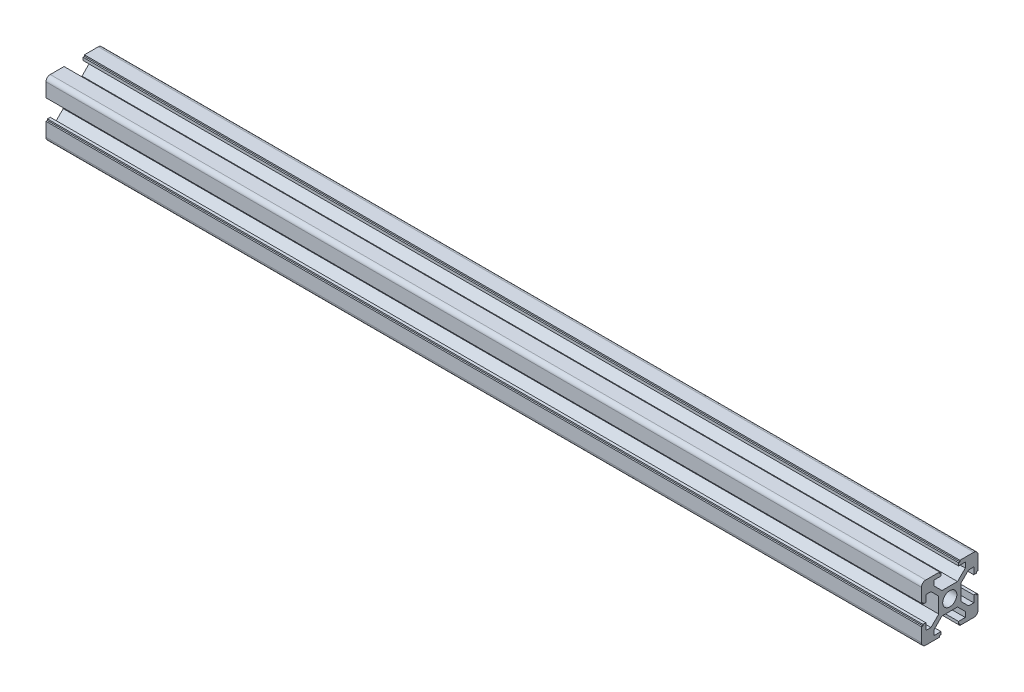
SolidWorks part; units mm, degrees
ref_plane "前视基准面" through (0, 0, 0) normal (0, 0, 1) x (1, 0, 0)
ref_plane "上视基准面" through (0, 0, 0) normal (0, 1, 0) x (1, 0, 0)
ref_plane "右视基准面" through (0, 0, 0) normal (1, 0, 0) x (0, 0, -1)
other "Configuration Table"
sketch "草图1" plane through (0, 0, 0) normal (0, 1, 0) x (1, 0, 0)
  line L0 (0, 0) -> (310, 0)
  dimension "D1" = 310
other "铝型材 20 X 20 X R1.5(1)"
ref_plane "基准面1" through (0, 0, 0) normal (1, 0, 0) x (0, 0, -1)
sketch "Sketch1" plane through (0, 0, 0) normal (1, 0, 0) x (0, 0, -1)
  line L0 (-3.6, 10) -> (-3.6, 9.5)
  line L1 (-3.6, 9.5) -> (-3.1, 9.5)
  line L2 (-3.1, 9.5) -> (-3.1, 8.5)
  line L3 (-3.1, 8.5) -> (-5.5, 8.5)
  line L4 (-8.5, -10) -> (-3.6, -10)
  line L5 (-10, -8.5) -> (-10, -3.6)
  line L6 (8.5, 10) -> (3.6, 10)
  line L7 (10, 8.5) -> (10, 3.6)
  line L8 (0, 14.8756) -> (0, 0) construction
  line L9 (0, 0) -> (14.1675, 0) construction
  line L10 (-5.5, 8.5) -> (-5.5, 6.65)
  line L11 (-5.5, 6.65) -> (-2.75, 3.9)
  line L12 (-2.75, 3.9) -> (2.75, 3.9)
  line L13 (5.5, 6.65) -> (2.75, 3.9)
  line L14 (5.5, 8.5) -> (5.5, 6.65)
  line L15 (3.1, 8.5) -> (5.5, 8.5)
  line L16 (3.1, 9.5) -> (3.1, 8.5)
  line L17 (3.6, 9.5) -> (3.1, 9.5)
  line L18 (3.6, 10) -> (3.6, 9.5)
  line L19 (-3.6, 10) -> (-8.5, 10)
  line L20 (10, 3.6) -> (9.5, 3.6)
  line L21 (9.5, 3.6) -> (9.5, 3.1)
  line L22 (9.5, 3.1) -> (8.5, 3.1)
  line L23 (8.5, 3.1) -> (8.5, 5.5)
  line L24 (8.5, 5.5) -> (6.65, 5.5)
  line L25 (6.65, 5.5) -> (3.9, 2.75)
  line L26 (3.9, 2.75) -> (3.9, -2.75)
  line L27 (6.65, -5.5) -> (3.9, -2.75)
  line L28 (8.5, -5.5) -> (6.65, -5.5)
  line L29 (8.5, -3.1) -> (8.5, -5.5)
  line L30 (9.5, -3.1) -> (8.5, -3.1)
  line L31 (9.5, -3.6) -> (9.5, -3.1)
  line L32 (10, -3.6) -> (9.5, -3.6)
  line L33 (3.6, -10) -> (3.6, -9.5)
  line L34 (3.6, -9.5) -> (3.1, -9.5)
  line L35 (3.1, -9.5) -> (3.1, -8.5)
  line L36 (3.1, -8.5) -> (5.5, -8.5)
  line L37 (5.5, -8.5) -> (5.5, -6.65)
  line L38 (5.5, -6.65) -> (2.75, -3.9)
  line L39 (2.75, -3.9) -> (-2.75, -3.9)
  line L40 (-5.5, -6.65) -> (-2.75, -3.9)
  line L41 (-5.5, -8.5) -> (-5.5, -6.65)
  line L42 (-3.1, -8.5) -> (-5.5, -8.5)
  line L43 (-3.1, -9.5) -> (-3.1, -8.5)
  line L44 (-3.6, -9.5) -> (-3.1, -9.5)
  line L45 (-3.6, -10) -> (-3.6, -9.5)
  line L46 (-10, -3.6) -> (-9.5, -3.6)
  line L47 (-9.5, -3.6) -> (-9.5, -3.1)
  line L48 (-9.5, -3.1) -> (-8.5, -3.1)
  line L49 (-8.5, -3.1) -> (-8.5, -5.5)
  line L50 (-8.5, -5.5) -> (-6.65, -5.5)
  line L51 (-6.65, -5.5) -> (-3.9, -2.75)
  line L52 (-3.9, -2.75) -> (-3.9, 2.75)
  line L53 (-6.65, 5.5) -> (-3.9, 2.75)
  line L54 (-8.5, 5.5) -> (-6.65, 5.5)
  line L55 (-8.5, 3.1) -> (-8.5, 5.5)
  line L56 (-9.5, 3.1) -> (-8.5, 3.1)
  line L57 (-9.5, 3.6) -> (-9.5, 3.1)
  line L58 (-10, 3.6) -> (-9.5, 3.6)
  line L59 (3.6, -10) -> (8.5, -10)
  line L60 (-10, 3.6) -> (-10, 8.5)
  line L61 (10, -3.6) -> (10, -8.5)
  circle A0 centre (0, 0) radius 2.5
  arc A1 (-10, 8.5) -> (-8.5, 10) centre (-8.5, 8.5) cw
  arc A2 (10, 8.5) -> (8.5, 10) centre (8.5, 8.5) ccw
  arc A3 (-8.5, -10) -> (-10, -8.5) centre (-8.5, -8.5) cw
  arc A4 (8.5, -10) -> (10, -8.5) centre (8.5, -8.5) ccw
  point P0 (-10, 0)
  point P1 (10, 0)
  point P2 (0, 10)
  point P3 (0, -10)
  point P4 (0, 0)
  point P5 (-10, -10)
  point P6 (10, -10)
  point P7 (10, 10)
  point P8 (-10, 10)
  point P13 (0, 0)
  point P36 (-10, 10)
  point P39 (10, 10)
  dimension "D1" = 11
  dimension "D2" = 20
  dimension "D3" = 6.2
  dimension "D4" = 7.2
  dimension "D5" = 6.1
  dimension "D6" = 5
  dimension "D7" = 1.5
  dimension "D8" = 45
  dimension "D9" = 0.5
  dimension "D10" = 1
  dimension "D11" = 5.5
